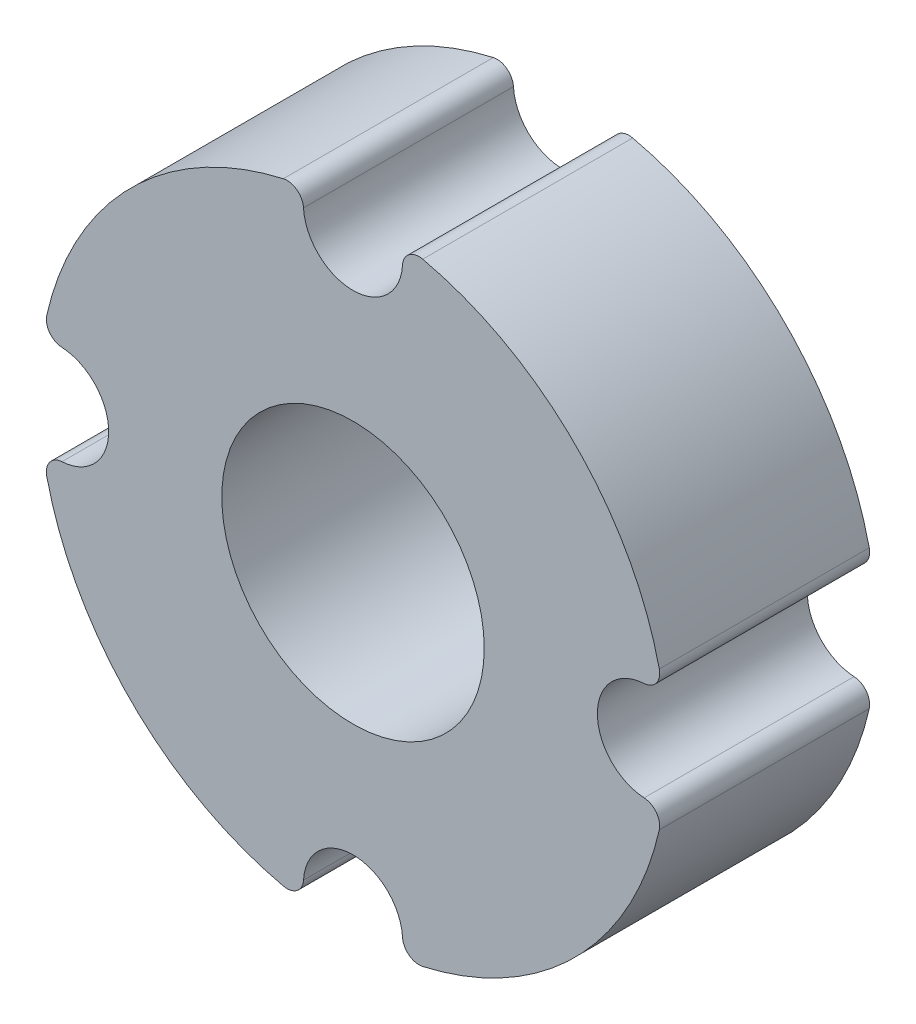
SolidWorks part; units mm, degrees
ref_plane "Front Plane" through (0, 0, 0) normal (0, 0, 1) x (1, 0, 0)
ref_plane "Top Plane" through (0, 0, 0) normal (0, 1, 0) x (1, 0, 0)
ref_plane "Right Plane" through (0, 0, 0) normal (1, 0, 0) x (0, 0, -1)
sketch "Sketch1" plane through (0, 0, 0) normal (0, 0, 1) x (1, 0, 0)
  circle A0 centre (0, 0) radius 9.5
  circle A1 centre (0, 0) radius 3.9688
extrude "Boss-Extrude1" add sketch "Sketch1" along normal blind 6.35
sketch "Sketch4" plane through (0, 0, 6.35) normal (0, 0, 1) x (1, 0, 0)
  line L0 (0, -55) -> (0, 55) construction
  point P0 (0, 8.89)
hole_wizard "Ø3.0mm Dowel Hole1" positions "Sketch4" profile "Sketch5" hole size "Ø3.0" standard "ANSI Metric" end condition through all
sketch "Sketch5" plane through (0, 8.89, 6.35) normal (1, 0, 0) x (0, -1, 0)
  line L0 (0, 0) -> (0, 6.35)
  line L1 (0, 6.35) -> (1.5, 6.35)
  line L2 (1.5, 6.35) -> (1.5, 0)
  line L5 (1.5, 0) -> (0, 0)
  line L11 (0, -6.35) -> (0, 107.95) construction
  dimension "Thru Hole Dia." = 3
  dimension "Thru Hole Depth" = 6.35
pattern_circular "CirPattern1" count 4 over 360 about axis through (0, 0, 0) along (0, 0, 1) of "Ø3.0mm Dowel Hole1"
fillet "Fillet1" radius 0.5 8 edges at (1.4127, -9.3944, 3.175) (-1.4127, -9.3944, 3.175) (-9.3944, -1.4127, 3.175) (-9.3944, 1.4127, 3.175) (9.3944, 1.4127, 3.175) (9.3944, -1.4127, 3.175) (-1.4127, 9.3944, 3.175) (1.4127, 9.3944, 3.175)
